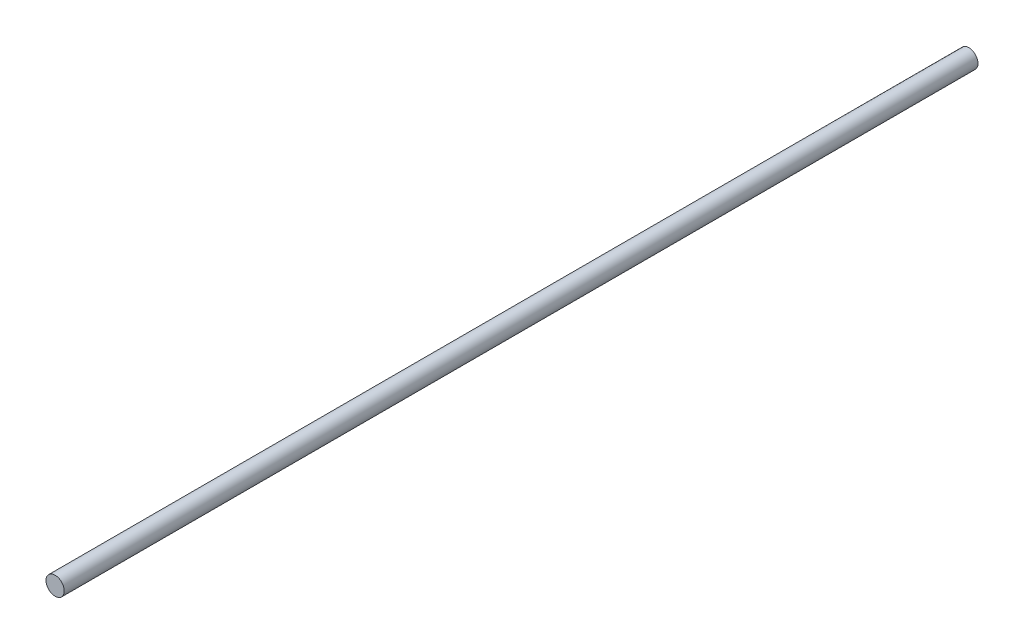
SolidWorks part; units mm, degrees
ref_plane "Face" through (0, 0, 0) normal (0, 0, 1) x (1, 0, 0)
ref_plane "Dessus" through (0, 0, 0) normal (0, 1, 0) x (1, 0, 0)
ref_plane "Droite" through (0, 0, 0) normal (1, 0, 0) x (0, 0, -1)
sketch "Esquisse1" plane through (0, 0, 0) normal (0, 0, 1) x (1, 0, 0)
  circle A0 centre (0, 0) radius 2.5
extrude "Boss.-Extru.1" add sketch "Esquisse1" along normal blind 250
